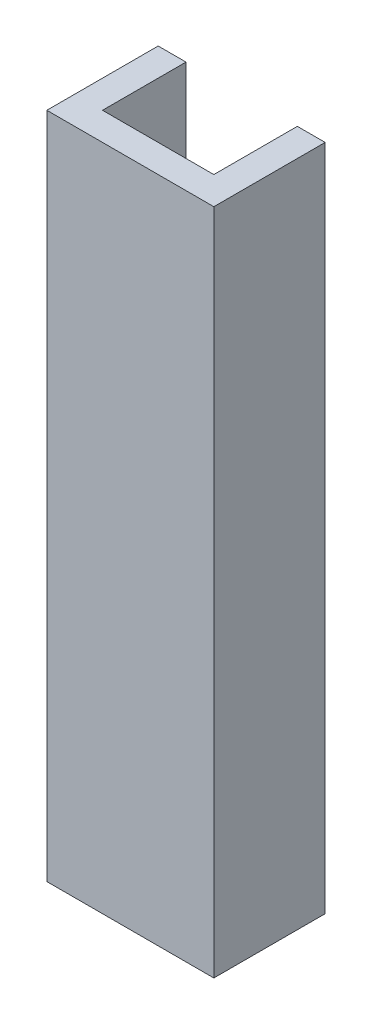
SolidWorks part; units mm, degrees
ref_plane "Front Plane" through (0, 0, 0) normal (0, 0, 1) x (1, 0, 0)
ref_plane "Top Plane" through (0, 0, 0) normal (0, 1, 0) x (1, 0, 0)
ref_plane "Right Plane" through (0, 0, 0) normal (1, 0, 0) x (0, 0, -1)
sketch "Sketch1" plane through (0, 0, 0) normal (0, 1, 0) x (1, 0, 0)
  line L0 (50.8, 0) -> (-50.8, 0)
  line L1 (-50.8, 0) -> (-50.8, 76.2)
  line L2 (-50.8, 76.2) -> (-76.2, 76.2)
  line L3 (-76.2, 76.2) -> (-76.2, -25.4)
  line L4 (-76.2, -25.4) -> (76.2, -25.4)
  line L5 (0, -25.4) -> (0, 0) construction
  line L6 (76.2, 76.2) -> (76.2, -25.4)
  line L7 (50.8, 76.2) -> (76.2, 76.2)
  line L8 (50.8, 0) -> (50.8, 76.2)
  dimension "D1" = 76.2
  dimension "D2" = 101.6
  dimension "D3" = 152.4
  dimension "D4" = 101.6
extrude "Extrude1" add sketch "Sketch1" along normal blind 609.6
sketch "Sketch2" plane through (0, 0, 0) normal (0, 0, -1) x (-1, 0, 0)
  line L0 (-50.8, 609.6) -> (50.8, 609.6) construction
  point P0 (0, 609.6)
ref_plane "Center plane" through (0, 0, 0) normal (1, 0, 0) x (0, 0, -1)
